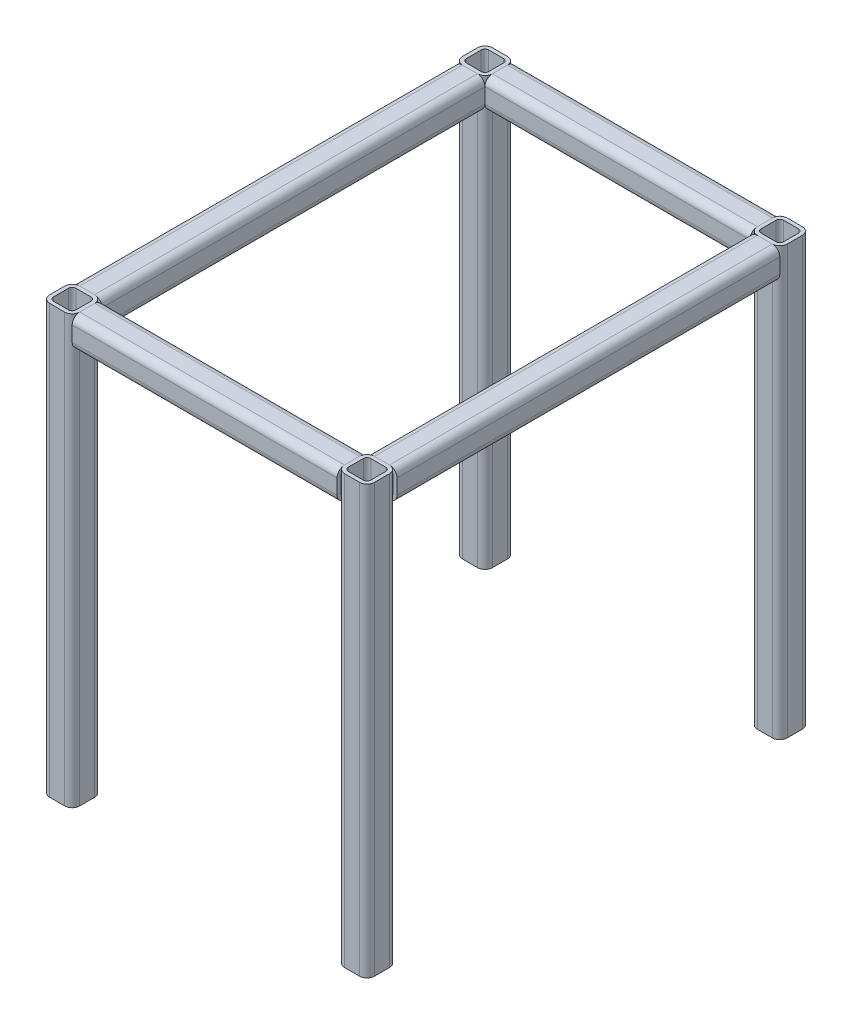
SolidWorks part; units mm, degrees
ref_plane "Front Plane" through (0, 0, 0) normal (0, 0, 1) x (1, 0, 0)
ref_plane "Top Plane" through (0, 0, 0) normal (0, 1, 0) x (1, 0, 0)
ref_plane "Right Plane" through (0, 0, 0) normal (1, 0, 0) x (0, 0, -1)
sketch3d "3DSketch1"
  line L0 (0, 0, 0) -> (0, -700, 0)
  line L1 (0, 0, 0) -> (500, 0, 0)
  line L2 (500, 0, 0) -> (500, -700, 0)
  line L3 (500, 0, 0) -> (500, 0, -700)
  line L4 (0, 0, 0) -> (0, 0, -700)
  line L5 (0, 0, -700) -> (500, 0, -700)
  line L6 (500, 0, -700) -> (500, -700, -700)
  line L7 (0, 0, -700) -> (0, -700, -700)
  dimension "D1" = 700
  dimension "D2" = 500
  dimension "D3" = 700
other "Square tube 2 X 2 X 0.25(1)"
ref_plane "Plane2" through (500, 0, 0) normal (0, -1, 0) x (1, 0, 0)
sketch "Sketch11" plane through (500, 0, 0) normal (0, -1, 0) x (1, 0, 0)
  line L0 (-12.7, -19.05) -> (12.7, -19.05)
  line L1 (-19.05, -12.7) -> (-19.05, 12.7)
  line L2 (12.7, 19.05) -> (-12.7, 19.05)
  line L3 (19.05, 12.7) -> (19.05, -12.7)
  line L4 (-12.7, -25.4) -> (12.7, -25.4)
  line L5 (-25.4, -12.7) -> (-25.4, 12.7)
  line L6 (12.7, 25.4) -> (-12.7, 25.4)
  line L7 (25.4, 12.7) -> (25.4, -12.7)
  line L8 (0, 0) -> (19.05, 0) construction
  line L9 (0, 0) -> (0, 19.05) construction
  arc A0 (25.4, 12.7) -> (12.7, 25.4) centre (12.7, 12.7) ccw
  arc A1 (12.7, -25.4) -> (25.4, -12.7) centre (12.7, -12.7) ccw
  arc A2 (-25.4, -12.7) -> (-12.7, -25.4) centre (-12.7, -12.7) ccw
  arc A3 (-12.7, 25.4) -> (-25.4, 12.7) centre (-12.7, 12.7) ccw
  arc A4 (-12.7, 19.05) -> (-19.05, 12.7) centre (-12.7, 12.7) ccw
  arc A5 (19.05, 12.7) -> (12.7, 19.05) centre (12.7, 12.7) ccw
  arc A6 (12.7, -19.05) -> (19.05, -12.7) centre (12.7, -12.7) ccw
  arc A7 (-19.05, -12.7) -> (-12.7, -19.05) centre (-12.7, -12.7) ccw
  point P3 (0, 25.4)
  point P4 (25.4, 0)
  point P5 (0, -25.4)
  point P6 (-25.4, 0)
  point P7 (-25.4, 25.4)
  point P8 (-25.4, -25.4)
  point P33 (0, 0)
  point P35 (25.4, -25.4)
  point P36 (25.4, 25.4)
  point P37 (0, 0)
  dimension "D1" = 12.7
  dimension "Thickness" = 6.35
  dimension "V_leg" = 50.8
other "Square tube 2 X 2 X 0.25(3)"
ref_plane "Plane4" through (500, 0, 0) normal (0, 0, -1) x (1, 0, 0)
sketch "Sketch1" plane through (500, 0, 0) normal (0, 0, -1) x (1, 0, 0)
  line L0 (-12.7, -19.05) -> (12.7, -19.05)
  line L1 (-19.05, -12.7) -> (-19.05, 12.7)
  line L2 (12.7, 19.05) -> (-12.7, 19.05)
  line L3 (19.05, 12.7) -> (19.05, -12.7)
  line L4 (-12.7, -25.4) -> (12.7, -25.4)
  line L5 (-25.4, -12.7) -> (-25.4, 12.7)
  line L6 (12.7, 25.4) -> (-12.7, 25.4)
  line L7 (25.4, 12.7) -> (25.4, -12.7)
  line L8 (0, 0) -> (19.05, 0) construction
  line L9 (0, 0) -> (0, 19.05) construction
  arc A0 (25.4, 12.7) -> (12.7, 25.4) centre (12.7, 12.7) ccw
  arc A1 (12.7, -25.4) -> (25.4, -12.7) centre (12.7, -12.7) ccw
  arc A2 (-25.4, -12.7) -> (-12.7, -25.4) centre (-12.7, -12.7) ccw
  arc A3 (-12.7, 25.4) -> (-25.4, 12.7) centre (-12.7, 12.7) ccw
  arc A4 (-12.7, 19.05) -> (-19.05, 12.7) centre (-12.7, 12.7) ccw
  arc A5 (19.05, 12.7) -> (12.7, 19.05) centre (12.7, 12.7) ccw
  arc A6 (12.7, -19.05) -> (19.05, -12.7) centre (12.7, -12.7) ccw
  arc A7 (-19.05, -12.7) -> (-12.7, -19.05) centre (-12.7, -12.7) ccw
  point P3 (0, 25.4)
  point P4 (25.4, 0)
  point P5 (0, -25.4)
  point P6 (-25.4, 0)
  point P7 (-25.4, 25.4)
  point P8 (-25.4, -25.4)
  point P33 (0, 0)
  point P35 (25.4, -25.4)
  point P36 (25.4, 25.4)
  point P37 (0, 0)
  dimension "D1" = 12.7
  dimension "Thickness" = 6.35
  dimension "V_leg" = 50.8
other "Trim/Extend1"
